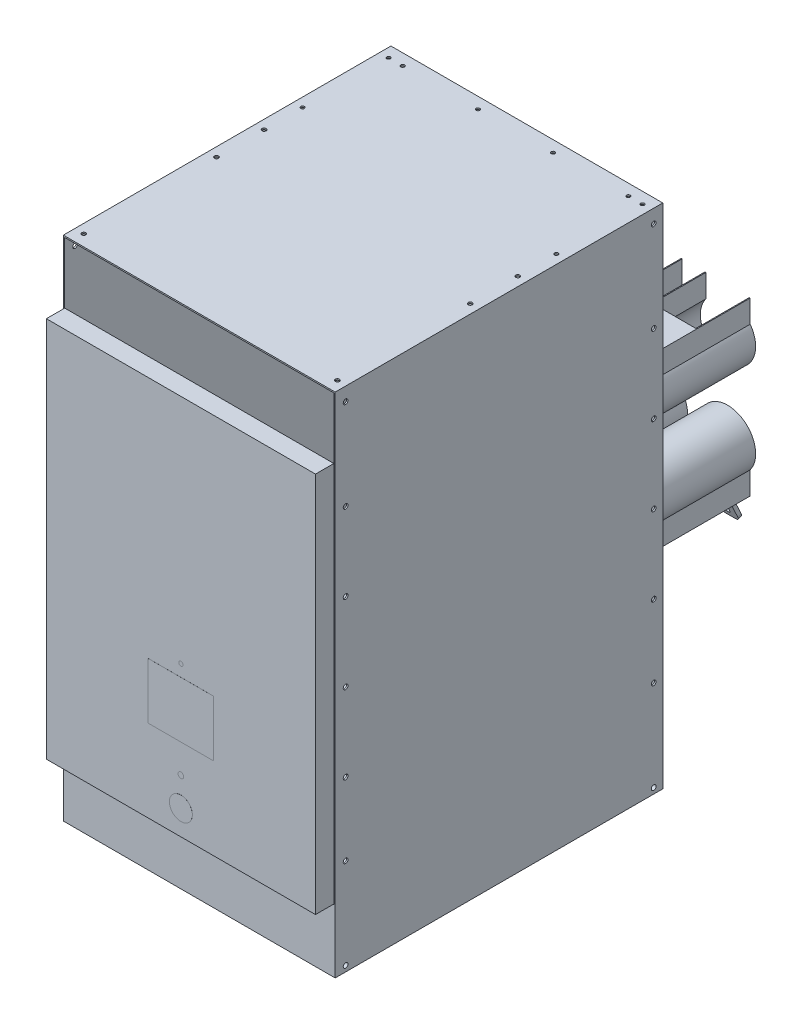
SolidWorks part; units mm, degrees
ref_plane "Alzado" through (0, 0, 0) normal (0, 0, 1) x (1, 0, 0)
ref_plane "Planta" through (0, 0, 0) normal (0, 1, 0) x (1, 0, 0)
ref_plane "Vista lateral" through (0, 0, 0) normal (1, 0, 0) x (0, 0, -1)
sketch "Croquis1" plane through (0, 0, 0) normal (0, 0, 1) x (1, 0, 0)
  line L1 (-300, 560) -> (300, 560)
  line L2 (-300, 560) -> (-300, -560)
  line L3 (-300, -560) -> (300, -560)
  line L4 (300, 560) -> (300, -560)
  line L5 (-300, 560) -> (300, -560) construction
  line L6 (-300, -560) -> (300, 560) construction
  point P0 (0, 0)
  dimension "D1" = 600
  dimension "D2" = 1120
extrude "Saliente-Extruir1" add sketch "Croquis1" against normal blind 723
shell "Vaciado1" thickness 3
sketch "Croquis2" plane through (0, 0, 0) normal (0, 0, 1) x (1, 0, 0)
  line L0 (300, -560) -> (300, -421)
  line L1 (300, -560) -> (300, 560) construction
  line L2 (300, -421) -> (-300, -421)
  line L3 (-300, 560) -> (-300, -560) construction
  line L4 (-300, -421) -> (-300, -560)
  line L5 (-300, -560) -> (300, -560)
  dimension "D1" = 139
extrude "Saliente-Extruir2" add sketch "Croquis2" against normal up to surface (720 mm away) up to face at (0, 0, -720)
sketch "Croquis3" plane through (0, 0, 0) normal (0, 0, 1) x (1, 0, 0)
  line L0 (-297, -421) -> (-297, -420)
  line L1 (-297, 557) -> (-297, -421) construction
  line L2 (-297, 557) -> (-297, -421) construction
  line L3 (-297, -420) -> (297, -420)
  line L4 (297, -421) -> (297, 557) construction
  line L5 (297, -420) -> (297, -421)
  line L6 (297, -421) -> (-297, -421)
  dimension "D1" = 1
extrude "Saliente-Extruir3" add sketch "Croquis3" along normal blind 1 separate body
sketch "Croquis4" plane through (0, 0, 0) normal (0, 0, 1) x (1, 0, 0)
  line L0 (-297, -420) -> (-297, 422)
  line L1 (-297, 557) -> (-297, -421) construction
  line L2 (-297, 422) -> (297, 422)
  line L3 (297, -421) -> (297, 557) construction
  line L4 (297, 422) -> (297, -420)
  line L5 (297, -420) -> (-297, -420)
  dimension "D1" = 842
extrude "Saliente-Extruir4" add sketch "Croquis4" along normal blind 40.5
sketch "Croquis5" plane through (0, 0, -723) normal (0, 0, -1) x (-1, 0, 0)
  line L0 (-300, 560) -> (-300, 95) construction
  line L1 (-300, -560) -> (-300, 560) construction
  line L2 (-300, 95) -> (300, 95) construction
  line L3 (300, 560) -> (300, -560) construction
  line L4 (0, 95) -> (0, 316.1052) construction
  line L5 (-300, 95) -> (0, 95) construction
  line L6 (0, 95) -> (-150, 95) construction
  line L7 (-150, 95) -> (-150, 203.2118) construction
  line L8 (0, 95) -> (300, 95) construction
  line L9 (300, 95) -> (150, 95) construction
  line L10 (150, 95) -> (150, 203.2118) construction
  line L11 (300, -560) -> (-300, -560) construction
  line L12 (-150, 95) -> (-150, -110) construction
  line L13 (-150, 95) -> (-150, -110) construction
  line L14 (-150, -110) -> (-150, -7.5) construction
  line L15 (-150, -7.5) -> (-180.043, -7.5) construction
  line L16 (0, -110) -> (-150, -110) construction
  circle A0 centre (-150, 95) radius 8
  circle A1 centre (0, 95) radius 8
  circle A2 centre (150, 95) radius 8
  circle A3 centre (-150, -110) radius 20.4612 construction
  circle A4 centre (-150, 95) radius 20.5 construction
  circle A5 centre (0, 95) radius 20.5 construction
  circle A6 centre (150, 95) radius 20.5 construction
  circle A7 centre (150, -110) radius 20.5 construction
  circle A8 centre (0, -110) radius 20.5 construction
  circle A9 centre (-150, -110) radius 20.5 construction
  circle A10 centre (150, -110) radius 8
  circle A11 centre (0, -110) radius 8
  circle A12 centre (-150, -110) radius 8
  dimension "D1" = 655
  dimension "D2" = 16
  dimension "D3" = 16
  dimension "D4" = 16
  dimension "D6" = 41
  dimension "D7" = 41
  dimension "D8" = 41
  dimension "D5" = 205
extrude "Cortar-Extruir1" cut sketch "Croquis5" against normal blind 2
sketch "Croquis7" plane through (0, 0, -723) normal (0, 0, -1) x (-1, 0, 0)
  line L0 (150, 95) -> (150, 181.6606) construction
  line L1 (198, 131) -> (198, 179.6606)
  line L2 (100, 131.6606) -> (100, 181.6606)
  line L3 (198, 179.6606) -> (102, 179.6606)
  line L4 (100, 131.6606) -> (200, 131.6606) construction
  line L5 (200, 131.6606) -> (200, 181.6606)
  line L6 (200, 181.6606) -> (100, 181.6606)
  line L7 (102, 131) -> (102, 179.6606)
  line L8 (-50, 131.6606) -> (-50, 181.6606)
  line L9 (50, 181.6606) -> (-50, 181.6606)
  line L10 (48, 179.6606) -> (-48, 179.6606)
  line L11 (50, 131.6606) -> (50, 181.6606)
  line L12 (48, 131) -> (48, 179.6606)
  line L13 (-200, 131.6606) -> (-200, 181.6606)
  line L14 (-100, 181.6606) -> (-200, 181.6606)
  line L15 (-102, 179.6606) -> (-198, 179.6606)
  line L16 (-100, 131.6606) -> (-100, 181.6606)
  line L17 (-102, 131) -> (-102, 179.6606)
  line L18 (-198, 179.6606) -> (-198, 131)
  line L19 (-48, 179.6606) -> (-48, 131)
  arc A0 (100, 131.6606) -> (200, 131.6606) centre (150, 95) ccw
  arc A1 (102, 131) -> (198, 131) centre (150, 95) ccw
  arc A2 (-50, 131.6606) -> (50, 131.6606) centre (0, 95) ccw
  arc A3 (-48, 131) -> (48, 131) centre (0, 95) ccw
  arc A4 (-200, 131.6606) -> (-100, 131.6606) centre (-150, 95) ccw
  arc A5 (-198, 131) -> (-102, 131) centre (-150, 95) ccw
  dimension "D1" = 124
  dimension "D2" = 50
  dimension "D3" = 2
  dimension "D4" = 3
extrude "Saliente-Extruir5" add sketch "Croquis7" along normal blind 293
sketch "Croquis8" plane through (0, 0, -723) normal (0, 0, -1) x (-1, 0, 0)
  line L0 (102, 179.6606) -> (102, 131)
  line L1 (198, 179.6606) -> (102, 179.6606) construction
  line L2 (102, 179.6606) -> (102, 131) construction
  line L3 (102, 179.6606) -> (198, 179.6606)
  line L4 (198, 179.6606) -> (198, 131)
  line L5 (-48, 179.6606) -> (-48, 131)
  line L6 (-48, 179.6606) -> (48, 179.6606)
  line L7 (48, 179.6606) -> (48, 131)
  line L8 (-198, 179.6606) -> (-198, 131)
  line L9 (-198, 179.6606) -> (-102, 179.6606)
  line L10 (-102, 179.6606) -> (-102, 131)
  circle A0 centre (150, 95) radius 8
  arc A1 (102, 131) -> (198, 131) centre (150, 95) ccw
  arc A2 (-48, 131) -> (48, 131) centre (0, 95) ccw
  arc A3 (-198, 131) -> (-102, 131) centre (-150, 95) ccw
  circle A4 centre (-150, 95) radius 8
  circle A5 centre (0, 95) radius 8
  dimension "D1" = 3
extrude "Saliente-Extruir7" add sketch "Croquis8" along normal blind 177
sketch "Croquis9" plane through (0, 181.6606, 0) normal (0, 1, 0) x (1, 0, 0)
  line L0 (100, 1016) -> (200, 1016) construction
  line L1 (198, 898) -> (102, 898)
  line L2 (198, 898) -> (198, 1014)
  line L3 (198, 1014) -> (102, 1014)
  line L4 (102, 898) -> (102, 1014)
  line L5 (198, 898) -> (102, 1014) construction
  line L6 (198, 1014) -> (102, 898) construction
  line L7 (200, 1016) -> (200, 723) construction
  line L8 (100, 1016) -> (100, 723) construction
  line L9 (48, 898) -> (48, 1014)
  line L10 (48, 898) -> (-48, 898)
  line L11 (-48, 898) -> (-48, 1014)
  line L12 (48, 1014) -> (-48, 1014)
  line L13 (-102, 898) -> (-102, 1014)
  line L14 (-102, 898) -> (-198, 898)
  line L15 (-198, 898) -> (-198, 1014)
  line L16 (-102, 1014) -> (-198, 1014)
  line L17 (198, 1014) -> (198, 1016)
  line L18 (102, 1014) -> (102, 1016)
  line L19 (48, 1014) -> (48, 1016)
  line L20 (-48, 1014) -> (-48, 1016)
  line L21 (-50, 1016) -> (50, 1016) construction
  line L22 (-48, 1016) -> (48, 1016)
  line L23 (102, 1016) -> (198, 1016)
  line L24 (-102, 1014) -> (-102, 1016)
  line L25 (-200, 1016) -> (-100, 1016) construction
  line L26 (-102, 1016) -> (-198, 1016)
  line L27 (-198, 1016) -> (-198, 1014)
  point P0 (150, 956)
  line M15 (200, 1016) -> (100, 1016)
  dimension "D1" = 2
  dimension "D2" = 2
  dimension "D3" = 2
  dimension "D4" = 116
  dimension "D5" = 3
extrude "Cortar-Extruir4" cut sketch "Croquis9" against normal blind 2 contours L13 L16 L15 L14 | L9 L12 L11 L10 | L4 L1 L2 L3 | L26 L27 L16 L24 | L22 L20 L12 L19 | L18 L3 L17 M15
sketch "Croquis10" plane through (0, 0, -900) normal (0, 0, -1) x (-1, 0, 0)
  circle A0 centre (-150, 95) radius 20.5
  circle A1 centre (0, 95) radius 20.5
  circle A2 centre (150, 95) radius 20.5
  circle A3 centre (-150, 95) radius 8
  circle A4 centre (0, 95) radius 8
  circle A5 centre (150, 95) radius 8
  dimension "D1" = 41
  dimension "D2" = 41
  dimension "D3" = 41
extrude "Saliente-Extruir8" add sketch "Croquis10" along normal blind 2
sketch "Croquis11" plane through (0, 0, -723) normal (0, 0, -1) x (-1, 0, 0)
  line L0 (-150, 95) -> (-150, -110) construction
  line L1 (-150, -110) -> (-150, -7.5) construction
  line L2 (-150, -7.5) -> (276.0548, -7.5) construction
ref_plane "Plano1" through (0, -7.5, 0) normal (0, -1, 0) x (-1, 0, 0)
mirror "Simetría1" about plane through (0, -7.5, 0) normal (0, -1, 0) of "Saliente-Extruir8", "Saliente-Extruir7", "Saliente-Extruir5", "Cortar-Extruir4"
sketch "Croquis12" plane through (0, 0, -900) normal (0, 0, -1) x (-1, 0, 0)
  line L0 (150, -110) -> (150, -160) construction
  line L2 (130, -160) -> (170, -160)
  line L3 (130, -160) -> (130, -168)
  line L4 (130, -168) -> (170, -168)
  line L5 (170, -160) -> (170, -168)
  line L6 (130, -160) -> (170, -168) construction
  line L7 (130, -168) -> (170, -160) construction
  point P3 (150, -164)
  dimension "D1" = 50
  dimension "D2" = 8
  dimension "D3" = 40
sketch3d "Croquis3D1"
  line L0 (-150, -164, -900) -> (-150, -164, -974.8204)
  line L1 (-150, -169.7572, -983.8757) -> (-150, -261.7976, -1027)
  line L2 (-150, -164, -900) -> (-150, -387.8657, -900) construction
  line L3 (154.2752, -48.1476, -1016) -> (154.2752, -48.1476, -1114.5291) construction
  arc A0 (-150, -164, -974.8204) -> (-150, -169.7572, -983.8757) centre (-150, -174, -974.8204) ccw
  arc A1 (200, -146.6606, -1016) -> (100, -146.6606, -1016) centre (150, -110, -1016) ccw construction
  point P7 (-150, -164, -981.1782)
  point P8 (-160, -174, -974.8204)
  point P12 (150, -110, -954)
  dimension "D2" = 10
  dimension "D3" = 108
  dimension "D1" = 127
sweep "Barrer1" add profiles "Croquis12" path "Croquis3D1"
fillet "Redondeo1" radius 10 2 edges at (-130, -261.7976, -1027) (-170, -261.7976, -1027)
pattern_linear "MatrizL1" count 3 spacing 150 along (1, 0, 0) of "Redondeo1", "Barrer1"
sketch "Croquis13" plane through (0, 0, -723) normal (0, 0, -1) x (-1, 0, 0)
  line L1 (-265.3242, -286.3609) -> (248.6016, -286.3609)
  line L2 (-265.3242, -286.3609) -> (-265.3242, -418.2611)
  line L3 (-265.3242, -418.2611) -> (248.6016, -418.2611)
  line L4 (248.6016, -286.3609) -> (248.6016, -418.2611)
  line L5 (-265.3242, -286.3609) -> (248.6016, -418.2611) construction
  line L6 (-265.3242, -418.2611) -> (248.6016, -286.3609) construction
  point P0 (-8.3613, -352.311)
extrude "Cortar-Extruir5" cut sketch "Croquis13" against normal blind 66
sketch "Croquis14" plane through (0, 0, 40.5) normal (0, 0, 1) x (1, 0, 0)
  line L1 (-72.2918, -115.011) -> (72.2918, -115.011)
  line L2 (-72.2918, -115.011) -> (-72.2918, -238.6675)
  line L3 (-72.2918, -238.6675) -> (72.2918, -238.6675)
  line L4 (72.2918, -115.011) -> (72.2918, -238.6675)
  line L5 (-72.2918, -115.011) -> (72.2918, -238.6675) construction
  line L6 (-72.2918, -238.6675) -> (72.2918, -115.011) construction
  circle A0 centre (0, -88.8019) radius 4.7137
  circle A1 centre (0, -302.0958) radius 6.1593
  circle A2 centre (0, -365.3095) radius 25.2951
  point P0 (0, -176.8393)
extrude "Saliente-Extruir9" add sketch "Croquis14" along normal blind 0.1
sketch "Croquis18" plane through (0, -560, 0) normal (0, -1, 0) x (1, 0, 0)
  line L0 (-300, -723) -> (-280, -723) construction
  line L1 (-300, -723) -> (300, -723) construction
  line L2 (-280, -723) -> (-280, -683) construction
  line L3 (-280, -683) -> (-280, 0) construction
  line L4 (-300, 0) -> (300, 0) construction
  line L5 (0, 0) -> (0, -208.7817) construction
  line L6 (300, 0) -> (300, -25) construction
  line L7 (300, -723) -> (300, 0) construction
  line L8 (300, -25) -> (-300, -25) construction
  line L9 (-300, -723) -> (-300, 0) construction
  circle A0 centre (-280, -500.5) radius 4
  circle A1 centre (-280, -318) radius 4
  circle A2 centre (-280, -40) radius 4
  circle A3 centre (-280, -683) radius 4
  circle A4 centre (280, -683) radius 4
  circle A5 centre (280, -40) radius 4
  circle A6 centre (280, -318) radius 4
  circle A7 centre (280, -500.5) radius 4
  circle A8 centre (235, -25) radius 5.25
  circle A9 centre (83, -25) radius 5.25
  circle A10 centre (-83, -25) radius 5.25
  circle A11 centre (-235, -25) radius 5.25
  dimension "D3" = 182.5
  dimension "D4" = 182.5
  dimension "D5" = 278
  dimension "D6" = 8
  dimension "D7" = 8
  dimension "D8" = 8
  dimension "D9" = 8
  dimension "D11" = 65
  dimension "D12" = 152
  dimension "D13" = 166
  dimension "D14" = 152
  dimension "D15" = 10.5
  dimension "D16" = 10.5
  dimension "D17" = 10.5
  dimension "D18" = 10.5
  dimension "D1" = 40
  dimension "D2" = 20
  dimension "D10" = 25
extrude "Cortar-Extruir8" cut sketch "Croquis18" against normal blind 57
sketch "Croquis19" plane through (0, 560, 0) normal (0, 1, 0) x (1, 0, 0)
  line L0 (300, 723) -> (280, 723) construction
  line L1 (300, 723) -> (-300, 723) construction
  line L2 (280, 723) -> (280, 0) construction
  line L3 (297, 0) -> (-297, 0) construction
  line L4 (0, 0) -> (0, 318) construction
  line L5 (-300, 723) -> (-300, 698) construction
  line L6 (-300, 723) -> (-300, 0) construction
  line L7 (-300, 698) -> (300, 698) construction
  line L8 (300, 723) -> (300, 0) construction
  line L9 (-280, 698) -> (-280, 0) construction
  circle A0 centre (280, 698) radius 4
  circle A1 centre (280, 508) radius 4
  circle A2 centre (280, 318) radius 4.5
  circle A3 centre (280, 25) radius 4.5
  circle A4 centre (280, 423) radius 4.5
  circle A5 centre (83, 698) radius 4
  circle A6 centre (-280, 698) radius 4
  circle A7 centre (249, 698) radius 4
  circle A8 centre (-83, 698) radius 4
  circle A9 centre (-249, 698) radius 4
  circle A10 centre (-280, 508) radius 4
  circle A11 centre (-280, 423) radius 4.5
  circle A12 centre (-280, 318) radius 4.5
  circle A13 centre (-280, 25) radius 4.5
  point P39 (-300, 710.5)
  dimension "D3" = 190
  dimension "D4" = 190
  dimension "D6" = 293
  dimension "D7" = 8
  dimension "D8" = 8
  dimension "D10" = 51
  dimension "D11" = 166
  dimension "D12" = 166
  dimension "D13" = 166
  dimension "D14" = 20
  dimension "D15" = 190
  dimension "D16" = 190
  dimension "D17" = 293
  dimension "D18" = 105
  dimension "D19" = 8
  dimension "D20" = 8
  dimension "D21" = 8
  dimension "D22" = 8
  dimension "D23" = 8
  dimension "D24" = 8
  dimension "D25" = 9
  dimension "D26" = 9
  dimension "D27" = 9
  dimension "D28" = 9
  dimension "D29" = 9
  dimension "D30" = 9
  dimension "D1" = 20
  dimension "D2" = 25
  dimension "D5" = 105
  dimension "D9" = 25
extrude "Cortar-Extruir9" cut sketch "Croquis19" against normal blind 16
sketch "Croquis20" plane through (-300, 0, 0) normal (-1, 0, 0) x (0, 0, 1)
  line L0 (-723, -560) -> (-703, -560) construction
  line L1 (-723, -560) -> (0, -560) construction
  line L2 (-703, -560) -> (-703, 560) construction
  line L3 (-723, 560) -> (0, 560) construction
  line L4 (-723, 560) -> (-723, -560) construction
  line L5 (-723, 560) -> (0, 560) construction
  line L6 (0, 560) -> (-361.5, 560) construction
  line L7 (-361.5, 560) -> (-361.5, -560) construction
  line L8 (-361.5, 560) -> (-363, 560) construction
  line L9 (-363, 560) -> (-363, -560) construction
  line L10 (-23, -560) -> (-23, 560) construction
  line L11 (-3, -560) -> (-23, -560) construction
  circle A0 centre (-703, -547.5) radius 5.25
  circle A1 centre (-703, -347.5) radius 5.25
  circle A2 centre (-703, -187.5) radius 5.25
  circle A3 centre (-703, 157.5) radius 5.25
  circle A4 centre (-703, 330) radius 5.25
  circle A5 centre (-703, 530) radius 5.25
  circle A6 centre (-703, -15) radius 5.25
  circle A7 centre (-23, -15) radius 5.25
  circle A8 centre (-23, 530) radius 5.25
  circle A9 centre (-23, 330) radius 5.25
  circle A10 centre (-23, 157.5) radius 5.25
  circle A11 centre (-23, -187.5) radius 5.25
  circle A12 centre (-23, -347.5) radius 5.25
  circle A13 centre (-23, -547.5) radius 5.25
  dimension "D3" = 200
  dimension "D4" = 160
  dimension "D5" = 172.5
  dimension "D6" = 172.5
  dimension "D7" = 172.5
  dimension "D8" = 200
  dimension "D9" = 10.5
  dimension "D10" = 10.5
  dimension "D11" = 10.5
  dimension "D12" = 10.5
  dimension "D13" = 10.5
  dimension "D14" = 10.5
  dimension "D15" = 10.5
  dimension "D1" = 20
  dimension "D2" = 12.5
  dimension "D16" = 1.5
extrude "Cortar-Extruir10" cut sketch "Croquis20" against normal blind 16
sketch "Croquis21" plane through (300, 0, 0) normal (1, 0, 0) x (0, 0, -1)
  line L0 (0, -560) -> (723, -560) construction
  line L1 (723, -560) -> (361.5, -560) construction
  line L2 (361.5, -560) -> (361.5, -515.5097) construction
  line L3 (361.5, -560) -> (360, -560) construction
  line L4 (360, -560) -> (360, -509.1024) construction
  line L5 (363, -560) -> (363, -511.8078) construction
  line L6 (703, -547.5) -> (723, -547.5) construction
  line L7 (723, -560) -> (723, 560) construction
  circle A0 centre (23, 530) radius 5.25
  circle A1 centre (23, 330) radius 5.25
  circle A2 centre (23, 157.5) radius 5.25
  circle A3 centre (23, -15) radius 5.25
  circle A4 centre (23, -187.5) radius 5.25
  circle A5 centre (23, -347.5) radius 5.25
  circle A6 centre (23, -547.5) radius 5.25
  circle A7 centre (703, -547.5) radius 5.25
  circle A8 centre (703, -347.5) radius 5.25
  circle A9 centre (703, -187.5) radius 5.25
  circle A10 centre (703, -15) radius 5.25
  circle A11 centre (703, 157.5) radius 5.25
  circle A12 centre (703, 330) radius 5.25
  circle A13 centre (703, 530) radius 5.25
  dimension "D1" = 1.5
  dimension "D2" = 1.5
extrude "Cortar-Extruir11" cut sketch "Croquis21" against normal blind 16
sketch "Croquis22" plane through (0, 349.1399, -745.1706) normal (0, 0.4243, -0.9055) x (-1, 0, 0)
  line L0 (150, -672.7974) -> (150, -656.7974) construction
  line L1 (160, -672.7974) -> (140, -672.7974) construction
  line L2 (150, -656.7974) -> (150, -647.7974) construction
  line L3 (145, -656.7974) -> (145, -647.7974)
  line L4 (155, -656.7974) -> (155, -647.7974)
  line L5 (0, -656.7974) -> (0, -647.7974) construction
  line L6 (-5, -656.7974) -> (-5, -647.7974)
  line L7 (5, -656.7974) -> (5, -647.7974)
  line L8 (-150, -656.7974) -> (-150, -647.7974) construction
  line L9 (-155, -656.7974) -> (-155, -647.7974)
  line L10 (-145, -656.7974) -> (-145, -647.7974)
  arc A0 (145, -656.7974) -> (155, -656.7974) centre (150, -656.7974) ccw
  arc A1 (155, -647.7974) -> (145, -647.7974) centre (150, -647.7974) ccw
  arc A2 (-5, -656.7974) -> (5, -656.7974) centre (0, -656.7974) ccw
  arc A3 (5, -647.7974) -> (-5, -647.7974) centre (0, -647.7974) ccw
  arc A4 (-155, -656.7974) -> (-145, -656.7974) centre (-150, -656.7974) ccw
  arc A5 (-145, -647.7974) -> (-155, -647.7974) centre (-150, -647.7974) ccw
  point P4 (150, -652.2974)
  point P12 (0, -652.2974)
  point P19 (-150, -652.2974)
  dimension "D1" = 16
  dimension "D2" = 25
  dimension "D3" = 10
  dimension "D4" = 3
extrude "Cortar-Extruir12" cut sketch "Croquis22" against normal blind 42
pattern_linear "MatrizL2" count 2 spacing 30 along (0, 0.9055, 0.4243) of "Cortar-Extruir12"
